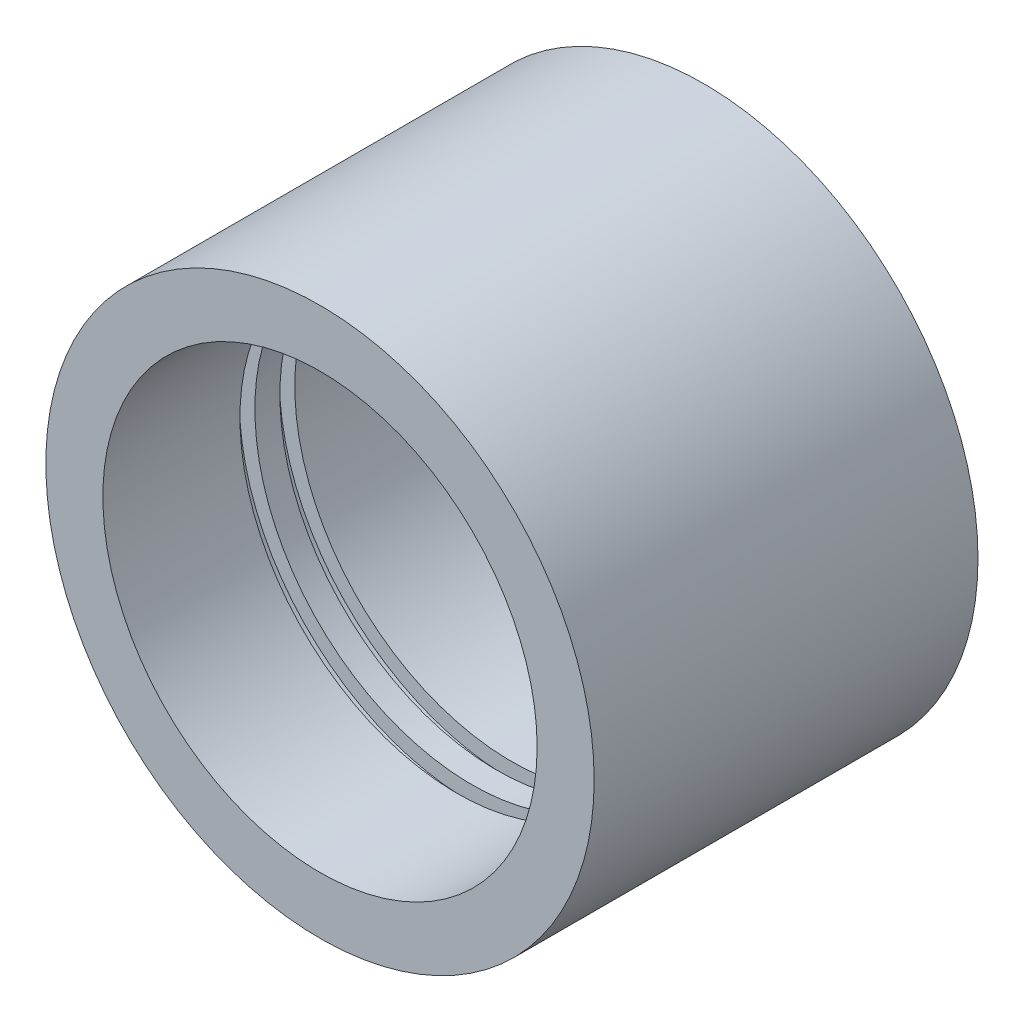
SolidWorks part; units mm, degrees
material "Plain Carbon Steel"
ref_plane "Front Plane" through (0, 0, 0) normal (0, 0, 1) x (1, 0, 0)
ref_plane "Top Plane" through (0, 0, 0) normal (0, 1, 0) x (1, 0, 0)
ref_plane "Right Plane" through (0, 0, 0) normal (1, 0, 0) x (0, 0, -1)
sketch "Sketch2" plane through (0, 0, 0) normal (1, 0, 0) x (0, 0, -1)
  line L0 (0, 25.146) -> (0, 31.75)
  line L1 (0, 31.75) -> (44.45, 31.75)
  line L2 (44.45, 31.75) -> (44.45, 19.05)
  line L3 (44.45, 19.05) -> (38.1, 19.05)
  line L4 (38.1, 19.05) -> (38.1, 25.146)
  line L5 (38.1, 25.146) -> (22.225, 25.146)
  line L6 (0, 0) -> (50000, 0) construction
  line L7 (15.875, 25.146) -> (15.875, 26.9494)
  line L8 (15.875, 26.9494) -> (17.6022, 26.9494)
  line L9 (17.6022, 26.9494) -> (17.6022, 25.146)
  line L10 (20.4978, 25.146) -> (20.4978, 26.9494)
  line L11 (20.4978, 26.9494) -> (22.225, 26.9494)
  line L12 (22.225, 26.9494) -> (22.225, 25.146)
  line L13 (15.875, 25.146) -> (0, 25.146)
  line L14 (20.4978, 25.146) -> (17.6022, 25.146)
  dimension "D1" = 31.75
  dimension "D2" = 25.146
  dimension "D3" = 6.35
  dimension "D4" = 38.1
  dimension "D5" = 26.9494
  dimension "D6" = 1.7272
  dimension "D7" = 6.35
  dimension "D8" = 15.875
  dimension "D9" = 19.05
revolve "Revolve1" add sketch "Sketch2" angle 360 about L6
